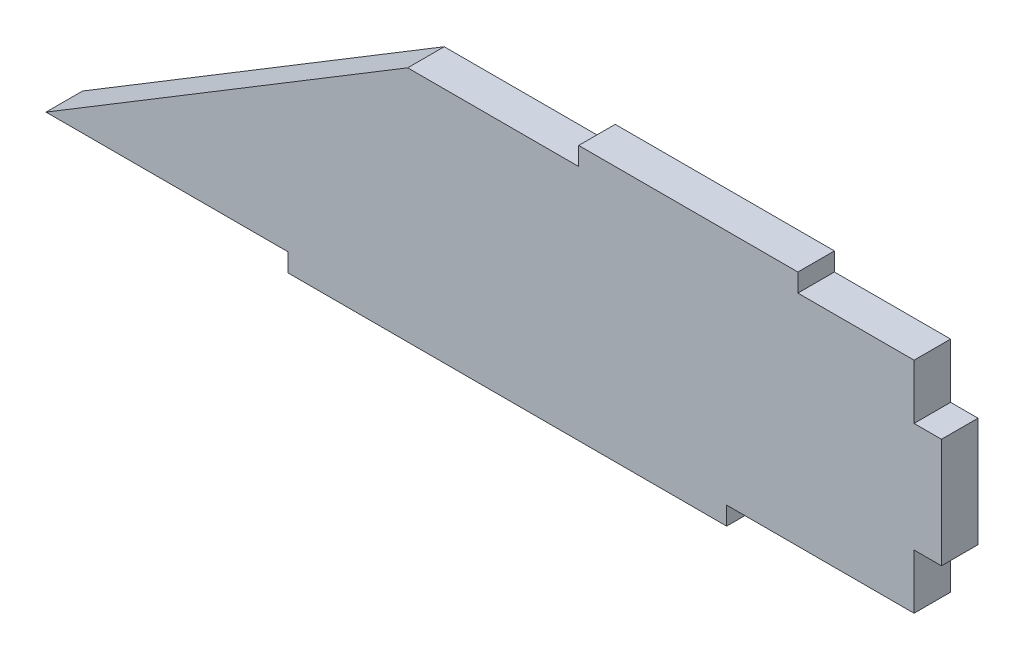
SolidWorks part; units mm, degrees
ref_plane "Front Plane" through (0, 0, 0) normal (0, 0, 1) x (1, 0, 0)
ref_plane "Top Plane" through (0, 0, 0) normal (0, 1, 0) x (1, 0, 0)
ref_plane "Right Plane" through (0, 0, 0) normal (1, 0, 0) x (0, 0, -1)
sketch "Sketch1" plane through (0, 0, 0) normal (0, 0, 1) x (1, 0, 0)
  line L0 (138.8804, 35.0708) -> (98.4944, 35.0708)
  line L1 (-162.8716, -41.1292) -> (-78.6706, -41.1292)
  line L4 (138.8804, -41.1292) -> (138.8804, -22.0792)
  line L5 (-162.8716, -41.1292) -> (138.8804, 35.0708) construction
  line L6 (-37.1416, 35.0708) -> (-162.8716, -41.1292)
  line L7 (-78.6706, -41.1292) -> (-78.6706, -47.4792)
  line L8 (-78.6706, -47.4792) -> (73.7294, -47.4792)
  line L9 (73.7294, -47.4792) -> (73.7294, -41.1292)
  line L10 (22.2944, 35.0708) -> (22.2944, 41.4208)
  line L11 (22.2944, 41.4208) -> (98.4944, 41.4208)
  line L12 (98.4944, 41.4208) -> (98.4944, 35.0708)
  line L15 (22.2944, 35.0708) -> (-37.1416, 35.0708)
  line L16 (73.7294, -41.1292) -> (138.8804, -41.1292)
  line L17 (138.8804, 16.0208) -> (148.4054, 16.0208)
  line L18 (138.8804, 16.0208) -> (138.8804, 35.0708)
  line L19 (148.4054, -22.0792) -> (138.8804, -22.0792)
  line L20 (148.4054, 16.0208) -> (148.4054, -22.0792) construction
  line L21 (148.4054, 16.0208) -> (148.4054, -22.0792)
  point P0 (0, 0)
  dimension "D2" = 301.752
  dimension "D3" = 76.2
  dimension "D4" = 6.35
  dimension "D5" = 152.4
  dimension "D6" = 6.35
  dimension "D7" = 76.2
  dimension "D8" = 40.386
  dimension "2.565" = 65.151
  dimension "D9" = 9.525
  dimension "D10" = 176.022
  dimension "D11" = 19.05
  dimension "D12" = 38.1
extrude "Boss-Extrude1" add sketch "Sketch1" along normal blind 12.7 contours L1 L7 L8 L9 L16 L4 L19 L21 L17 L18 L0 L12 L11 L10 L15 L6
